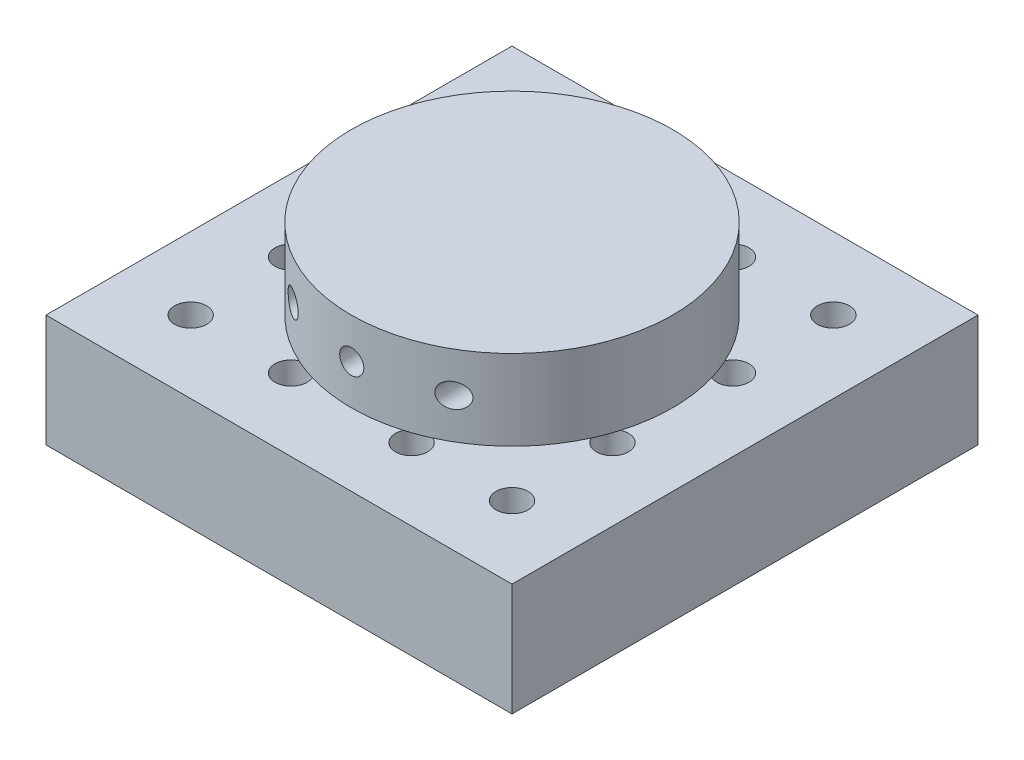
SolidWorks part; units mm, degrees
ref_plane "前视基准面" through (0, 0, 0) normal (0, 0, 1) x (1, 0, 0)
ref_plane "上视基准面" through (0, 0, 0) normal (0, 1, 0) x (1, 0, 0)
ref_plane "右视基准面" through (0, 0, 0) normal (1, 0, 0) x (0, 0, -1)
sketch "草图4" plane through (0, 0, 0) normal (0, 1, 0) x (1, 0, 0)
  line L1 (-29, 29) -> (29, 29)
  line L2 (-29, 29) -> (-29, -29)
  line L3 (-29, -29) -> (29, -29)
  line L4 (29, 29) -> (29, -29)
  line L5 (-29, 29) -> (29, -29) construction
  line L6 (-29, -29) -> (29, 29) construction
  point P0 (0, 0)
  dimension "D1" = 58
  dimension "D2" = 58
extrude "凸台-拉伸3" add sketch "草图4" along normal blind 14
sketch "草图6" plane through (0, 14, 0) normal (0, 1, 0) x (1, 0, 0)
  circle A0 centre (0, 0) radius 20
  dimension "D1" = 40
extrude "凸台-拉伸4" add sketch "草图6" along normal blind 10
sketch "草图7" plane through (0, 0, 0) normal (0, 0, 1) x (1, 0, 0)
  line L0 (-20, 19) -> (-10, 19)
  line L1 (-20, 24) -> (-20, 14) construction
  line L2 (20, 19) -> (10, 19)
  line L3 (20, 14) -> (20, 24) construction
  line L4 (-10, 19) -> (0, 19)
  circle A0 centre (-10, 19) radius 1.5
  circle A1 centre (10, 19) radius 1.5
  circle A2 centre (0, 19) radius 1.5
  dimension "D3" = 3
  dimension "D4" = 10
  dimension "D5" = 3
  dimension "D6" = 3
  dimension "D1" = 10
  dimension "D2" = 10
extrude "切除-拉伸1" cut sketch "草图7" against normal blind 30 and the other way blind 30
sketch "草图8" plane through (0, 0, 0) normal (0, -1, 0) x (1, 0, 0)
  line L0 (-7.5, 7.5) -> (-20, 7.5)
  line L1 (-7.5, 7.5) -> (7.5, 7.5)
  line L2 (-7.5, 7.5) -> (-7.5, -7.5)
  line L3 (-7.5, -7.5) -> (7.5, -7.5)
  line L4 (7.5, 7.5) -> (7.5, -7.5)
  line L5 (-7.5, 7.5) -> (7.5, -7.5) construction
  line L6 (-7.5, -7.5) -> (7.5, 7.5) construction
  line L7 (-20, 20) -> (20, 20)
  line L8 (-20, 20) -> (-20, -20)
  line L9 (-20, -20) -> (20, -20)
  line L10 (20, 20) -> (20, -20)
  line L11 (-20, 20) -> (20, -20) construction
  line L12 (-20, -20) -> (20, 20) construction
  line L13 (-7.5, 7.5) -> (-7.5, 20)
  line L14 (7.5, 7.5) -> (7.5, 20)
  line L15 (7.5, 7.5) -> (20, 7.5)
  line L16 (-7.5, -7.5) -> (-20, -7.5)
  line L17 (-7.5, -7.5) -> (-7.5, -20)
  line L18 (7.5, -7.5) -> (7.5, -20)
  line L19 (7.5, -7.5) -> (20, -7.5)
  circle A0 centre (-7.5, 7.5) radius 2
  circle A1 centre (7.5, 7.5) radius 2
  circle A2 centre (-20, 20) radius 2
  circle A3 centre (20, 20) radius 2
  circle A4 centre (-20, -20) radius 2
  circle A5 centre (-7.5, -7.5) radius 2
  circle A6 centre (7.5, -7.5) radius 2
  circle A7 centre (20, -20) radius 2
  circle A8 centre (-20, 7.5) radius 2
  circle A9 centre (-20, -7.5) radius 2
  circle A10 centre (-7.5, -20) radius 2
  circle A11 centre (7.5, -20) radius 2
  circle A12 centre (20, -7.5) radius 2
  circle A13 centre (20, 7.5) radius 2
  circle A14 centre (-7.5, 20) radius 2
  circle A15 centre (7.5, 20) radius 2
  point P0 (0, 0)
  point P6 (0, 0)
  dimension "D5" = 4
  dimension "D6" = 4
  dimension "D7" = 4
  dimension "D8" = 4
  dimension "D9" = 4
  dimension "D10" = 4
  dimension "D11" = 4
  dimension "D12" = 4
  dimension "D13" = 4
  dimension "D14" = 4
  dimension "D15" = 4
  dimension "D16" = 4
  dimension "D17" = 4
  dimension "D18" = 4
  dimension "D19" = 4
  dimension "D20" = 4
  dimension "D1" = 40
  dimension "D2" = 40
  dimension "D3" = 15
  dimension "D4" = 15
extrude "切除-拉伸2" cut sketch "草图8" against normal blind 14 contours A2 | A8 | A9 | A4 | A10 | A5 | A0 | A14 | A15 | A3 | A1 | A6 | A11 | A7 | A12 | A13
